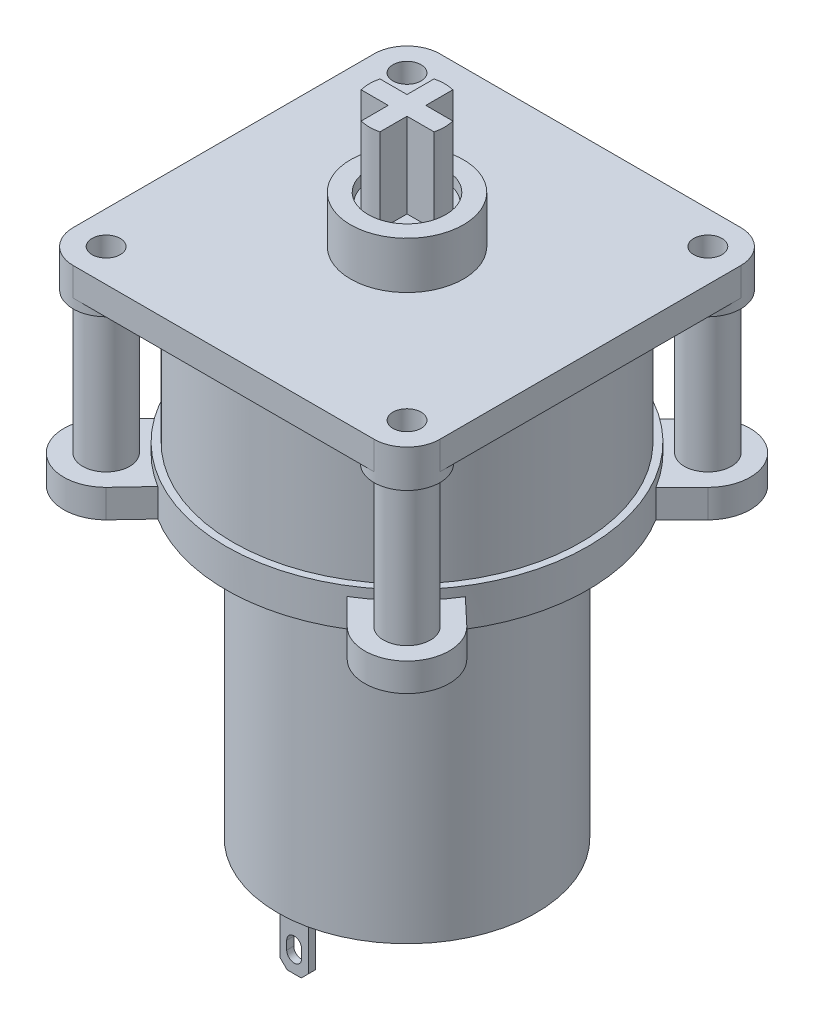
SolidWorks part; units mm, degrees
ref_plane "Front Plane" through (0, 0, 0) normal (0, 0, 1) x (1, 0, 0)
ref_plane "Top Plane" through (0, 0, 0) normal (0, 1, 0) x (1, 0, 0)
ref_plane "Right Plane" through (0, 0, 0) normal (1, 0, 0) x (0, 0, -1)
sketch "Sketch1" plane through (0, 0, 0) normal (0, 1, 0) x (1, 0, 0)
  circle A0 centre (0, 0) radius 13.75
  dimension "D1" = 27.5
extrude "motor_body" add sketch "Sketch1" along normal blind 32.5
sketch "Sketch7" plane through (0, 0, 0) normal (0, -1, 0) x (1, 0, 0)
  circle A0 centre (0, 0) radius 5
  dimension "D1" = 10
extrude "motor_tip" add sketch "Sketch7" along normal blind 3
sketch "Sketch8" plane through (0, 0, 0) normal (0, -1, 0) x (1, 0, 0)
  line L0 (0, 0) -> (9.5829, 0) construction
  line L1 (-1.5, 12) -> (1.5, 12)
  line L2 (-1.5, 12) -> (-1.5, 11.25)
  line L3 (-1.5, 11.25) -> (1.5, 11.25)
  line L4 (1.5, 12) -> (1.5, 11.25)
  line L5 (-1.5, 12) -> (1.5, 11.25) construction
  line L6 (-1.5, 11.25) -> (1.5, 12) construction
  line L7 (-1.5, -11.25) -> (1.5, -12) construction
  line L8 (-1.5, -12) -> (1.5, -11.25) construction
  line L9 (1.5, -12) -> (1.5, -11.25)
  line L10 (-1.5, -11.25) -> (1.5, -11.25)
  line L11 (-1.5, -12) -> (-1.5, -11.25)
  line L12 (-1.5, -12) -> (1.5, -12)
  point P0 (0, 11.625)
  point P13 (0, -11.625)
  dimension "D1" = 3
  dimension "D2" = 0.75
  dimension "D3" = 0
  dimension "D4" = 12
extrude "motor_contacts" add sketch "Sketch8" along normal blind 6.5
chamfer "motor_contacts_chamfer" distance 0.75 angle 45 4 edges at (1.5, -6.5, -11.625) (-1.5, -6.5, -11.625) (-1.5, -6.5, 11.625) (1.5, -6.5, 11.625)
sketch "Sketch9" plane through (0, 0, 12) normal (0, 0, 1) x (1, 0, 0)
  line L5 (0, -3.7937) -> (0, -4.7063) construction
  line L6 (0.7937, -3.7937) -> (0.7938, -4.7063)
  line L7 (-0.7937, -3.7937) -> (-0.7937, -4.7063)
  line L8 (0.75, -6.5) -> (-0.75, -6.5) construction
  arc A0 (0.7937, -3.7937) -> (-0.7937, -3.7937) centre (0, -3.7937) ccw
  arc A1 (-0.7937, -4.7063) -> (0.7938, -4.7063) centre (0, -4.7063) ccw
  point P2 (0, -4.25)
  point P8 (0, -5.5)
  point P11 (0, -3)
  dimension "D1" = 1
  dimension "D2" = 2.5
  dimension "D3" = 1.5875
extrude "motor_contacts_hole" cut sketch "Sketch9" against normal up to surface (23.25 mm away)
mirror "motor_contacts_hole2" about plane through (0, 0, 0) normal (0, 0, 1) of "motor_contacts_hole"
sketch "Sketch2" plane through (0, 32.5, 0) normal (0, 1, 0) x (1, 0, 0)
  line L0 (0, 27.311) -> (0, -26.2315) construction
  line L5 (-24.4427, 0) -> (26.9581, 0) construction
  line L6 (0, 0) -> (-16, 16) construction
  line L7 (-19.182, 12.818) -> (-12.818, 19.182) construction
  line L12 (-16, 16) -> (0, 0) construction
  line L13 (19.182, 12.818) -> (16.4166, 10.0527)
  line L14 (-19.182, 12.818) -> (-16.3552, 10.1523)
  line L15 (-12.818, 19.182) -> (-10.0527, 16.4166)
  line L16 (12.818, 19.182) -> (10.1523, 16.3552)
  line L17 (12.818, 19.182) -> (19.182, 12.818) construction
  line L18 (12.818, -19.182) -> (10.0527, -16.4166)
  line L19 (19.182, -12.818) -> (16.3552, -10.1523)
  line L20 (19.182, -12.818) -> (12.818, -19.182) construction
  line L21 (-19.182, -12.818) -> (-16.4166, -10.0527)
  line L22 (-12.818, -19.182) -> (-10.1523, -16.3552)
  line L23 (-12.818, -19.182) -> (-19.182, -12.818) construction
  arc A0 (-16.3552, 10.1523) -> (-16.4166, -10.0527) centre (0, 0) ccw
  arc A1 (-12.818, 19.182) -> (-19.182, 12.818) centre (-16, 16) ccw
  arc A2 (19.182, 12.818) -> (12.818, 19.182) centre (16, 16) ccw
  arc A3 (12.818, -19.182) -> (19.182, -12.818) centre (16, -16) ccw
  arc A4 (-19.182, -12.818) -> (-12.818, -19.182) centre (-16, -16) ccw
  arc A5 (10.1523, 16.3552) -> (-10.0527, 16.4166) centre (0, 0) ccw
  arc A6 (16.3552, -10.1523) -> (16.4166, 10.0527) centre (0, 0) ccw
  arc A7 (-10.1523, -16.3552) -> (10.0527, -16.4166) centre (0, 0) ccw
  point P29 (0, 0)
  dimension "D1" = 38.5
  dimension "D3" = 9
  dimension "D2" = 45
  dimension "D4" = 4
  dimension "D5" = 16
extrude "connection_bot_1" add sketch "Sketch2" along normal blind 3
sketch "Sketch14" plane through (0, 35.5, 0) normal (0, 1, 0) x (1, 0, 0)
  circle A0 centre (0, 0) radius 19.25
  dimension "D1" = 38.5
extrude "connection_bot_2" add sketch "Sketch14" along normal blind 1
sketch "Sketch10" plane through (0, 36.5, 0) normal (0, 1, 0) x (1, 0, 0)
  circle A0 centre (0, 0) radius 18.5
  dimension "D1" = 37
extrude "connection_mid" add sketch "Sketch10" along normal blind 15
sketch "Sketch11" plane through (0, 51.5, 0) normal (0, 1, 0) x (1, 0, 0)
  line L12 (-16, 19.5) -> (16, 19.5)
  line L13 (19.5, 16) -> (19.5, -16)
  line L14 (16, -19.5) -> (-16, -19.5)
  line L15 (-19.5, -16) -> (-19.5, 16)
  arc A9 (-16, 19.5) -> (-19.5, 16) centre (-16, 16) ccw
  arc A10 (19.5, 16) -> (16, 19.5) centre (16, 16) ccw
  arc A11 (16, -19.5) -> (19.5, -16) centre (16, -16) ccw
  arc A12 (-19.5, -16) -> (-16, -19.5) centre (-16, -16) ccw
  point P2 (0, 0)
  point P13 (0, 0)
  point P14 (0, 0)
  dimension "D3" = 7
  dimension "D1" = 16
  dimension "D2" = 16
extrude "connection_top_1" add sketch "Sketch11" along normal blind 3
sketch "Sketch12" plane through (0, 51.5, 0) normal (0, -1, 0) x (1, 0, 0)
  circle A1 centre (-16, 16) radius 3.5
  circle A5 centre (16, 16) radius 3.5
  circle A6 centre (16, -16) radius 3.5
  circle A7 centre (-16, -16) radius 3.5
  point P3 (0, 0)
  point P4 (0, 0)
  point P6 (0, 0)
  point P15 (0, 0)
  point P16 (0, 0)
  dimension "D1" = 16
  dimension "D3" = 7
  dimension "D2" = 16
extrude "connection_top_2" add sketch "Sketch12" along normal blind 1
sketch "Sketch13" plane through (0, 35.5, 0) normal (0, 1, 0) x (1, 0, 0)
  circle A4 centre (-16, -16) radius 2.5
  circle A5 centre (-16, 16) radius 2.5
  circle A6 centre (16, 16) radius 2.5
  circle A7 centre (16, -16) radius 2.5
  point P13 (0, 0)
  dimension "D1" = 5
  dimension "D2" = 16
  dimension "D3" = 16
extrude "screw_holders" add sketch "Sketch13" along normal up to surface (15 mm away) up to face at (-16, 50.5, 12.5)
sketch "Sketch3" plane through (0, 54.5, 0) normal (0, 1, 0) x (1, 0, 0)
  circle A0 centre (-16, 16) radius 1.5
  circle A1 centre (16, 16) radius 1.5
  circle A2 centre (16, -16) radius 1.5
  circle A3 centre (-16, -16) radius 1.5
  point P2 (0, 0)
  point P15 (0, 0)
  dimension "D1" = 3
  dimension "D2" = 4
  dimension "D3" = 16
  dimension "D4" = 16
extrude "screw_holes" cut sketch "Sketch3" against normal up to surface (22 mm away) up to face at (0, 32.5, 13.75)
sketch "Sketch15" plane through (0, 54.5, 0) normal (0, 1, 0) x (1, 0, 0)
  circle A0 centre (0, 0) radius 6
  circle A1 centre (0, 0) radius 4.125
  dimension "D1" = 12
  dimension "D2" = 8.25
extrude "motor_shaft_guide_" add sketch "Sketch15" along normal blind 5
sketch "Sketch16" plane through (0, 54.5, 0) normal (0, 1, 0) x (1, 0, 0)
  circle A0 centre (0, 0) radius 4
  dimension "D1" = 8
extrude "motor_shaft_bot" add sketch "Sketch16" along normal offset from surface (4 mm away) 1 up to face at (0, 59.5, 6)
sketch "Sketch17" plane through (0, 58.5, 0) normal (0, 1, 0) x (1, 0, 0)
  line L0 (-1, -1) -> (-1, -3.873)
  line L2 (-3.873, -1) -> (-1, -1)
  line L3 (-3.873, 1) -> (-1, 1)
  line L4 (-1, 3.873) -> (-1, 1)
  line L5 (1, 3.873) -> (1, 1)
  line L9 (1, 1) -> (3.873, 1)
  line L13 (1, -1) -> (1, -3.873)
  line L14 (1, -1) -> (3.873, -1)
  arc A0 (1, 3.873) -> (-1, 3.873) centre (0, 0) ccw
  arc A1 (3.873, -1) -> (3.873, 1) centre (0, 0) ccw
  arc A2 (-1, -3.873) -> (1, -3.873) centre (0, 0) ccw
  arc A3 (-3.873, 1) -> (-3.873, -1) centre (0, 0) ccw
  dimension "D1" = 8
  dimension "D2" = 2
  dimension "D3" = 2
extrude "motor_shaft_" add sketch "Sketch17" along normal blind 9
